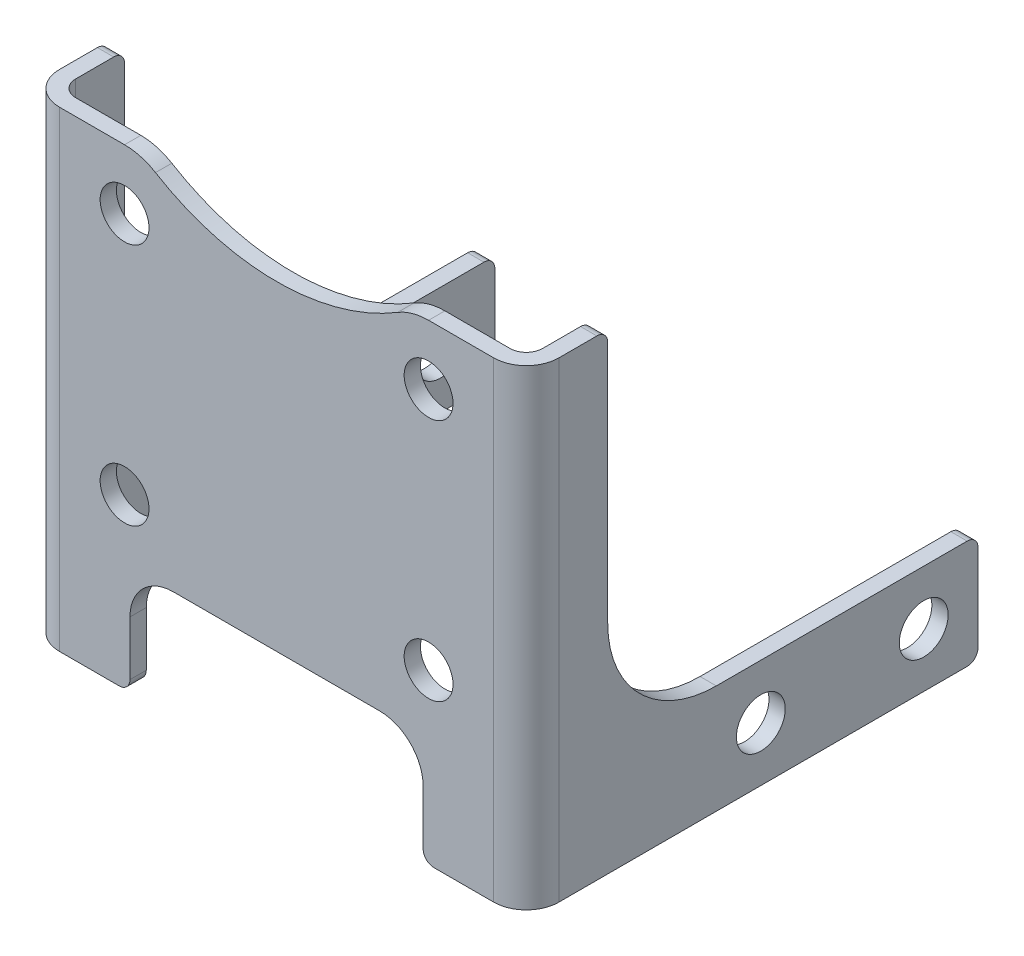
SolidWorks part; units mm, degrees
ref_plane "前视基准面" through (0, 0, 0) normal (0, 0, 1) x (1, 0, 0)
ref_plane "上视基准面" through (0, 0, 0) normal (0, 1, 0) x (1, 0, 0)
ref_plane "右视基准面" through (0, 0, 0) normal (1, 0, 0) x (0, 0, -1)
ref_plane "基准面1" through (0, 0, -40.1) normal (0, 0, -1) x (-1, 0, 0)
sketch "草图1" plane through (0, 0, -40.1) normal (0, 0, -1) x (-1, 0, 0)
  line L0 (-23, -17.5868) -> (-23, -61)
  line L1 (-23, -61) -> (23, -61)
  line L2 (23, -61) -> (23, -17.5868)
  line L3 (23, -17.5868) -> (-23, -17.5868)
extrude "凸台-拉伸1" add sketch "草图1" against normal blind 41.6
sketch "草图2" plane through (0, -61, 0) normal (0, -1, 0) x (1, 0, 0)
  line L0 (-21.5, -40.1) -> (21.5, -40.1)
  line L1 (21.5, -40.1) -> (21.5, 0)
  line L2 (21.5, 0) -> (-21.5, 0)
  line L3 (-21.5, 0) -> (-21.5, -40.1)
extrude "切除-拉伸1" cut sketch "草图2" against normal through all
sketch "草图3" plane through (0, 0, 1.5) normal (0, 0, 1) x (1, 0, 0)
  line L0 (-13.5, -61) -> (13.5, -61)
  line L1 (13.5, -61) -> (13.5, -51)
  line L2 (13.5, -51) -> (-13.5, -51)
  line L3 (-13.5, -51) -> (-13.5, -61)
extrude "切除-拉伸2" cut sketch "草图3" against normal through all
sketch "草图4" plane through (-21.5, 0, 0) normal (1, 0, 0) x (0, 0, -1)
  line L0 (40.1, -17.5868) -> (6, -17.5868)
  line L1 (6, -17.5868) -> (6, -51)
  line L2 (6, -51) -> (40.1, -51)
  line L3 (40.1, -51) -> (40.1, -17.5868)
extrude "切除-拉伸3" cut sketch "草图4" against normal through all
sketch "草图5" plane through (23, 0, 0) normal (1, 0, 0) x (0, 0, -1)
  line L0 (40.1, -17.5868) -> (6, -17.5868)
  line L1 (6, -17.5868) -> (6, -51)
  line L2 (6, -51) -> (40.1, -51)
  line L3 (40.1, -51) -> (40.1, -17.5868)
extrude "切除-拉伸4" cut sketch "草图5" against normal through all
sketch "草图6" plane through (0, 0, 1.5) normal (0, 0, 1) x (1, 0, 0)
  line L0 (12.3675, -17.5868) -> (-12.3675, -17.5868)
  arc A0 (-12.3675, -17.5868) -> (12.3675, -17.5868) centre (0, 0) ccw
extrude "切除-拉伸5" cut sketch "草图6" against normal through all
hole_wizard "Ø4.5 (4.5) 直径孔1" positions "草图8" profile "草图7" hole size "Ø4.5" standard "ANSI Metric"
sketch "草图8" plane through (-21.5, 0, 0) normal (1, 0, 0) x (0, 0, -1)
  point P0 (20.1, -56)
  point P1 (35.1, -56)
sketch "草图7" plane through (-21.5, -56, -20.1) normal (0, 1, 0) x (0, 0, -1)
  line L0 (0, 0) -> (0, 1.5)
  line L1 (0, 1.5) -> (2.25, 1.5)
  line L2 (2.25, 1.5) -> (2.25, 0)
  line L5 (2.25, 0) -> (0, 0)
  line L11 (0, -6.35) -> (0, 107.95) construction
  dimension "通孔孔直径" = 4.5
  dimension "通孔孔深度" = 1.5
hole_wizard "Ø4.5 (4.5) 直径孔2" positions "草图10" profile "草图9" hole size "Ø4.5" standard "ANSI Metric"
sketch "草图10" plane through (21.5, 0, 0) normal (-1, 0, 0) x (0, 0, 1)
  point P0 (-20.1, -56)
  point P1 (-35.1, -56)
sketch "草图9" plane through (21.5, -56, -20.1) normal (0, 1, 0) x (0, 0, 1)
  line L0 (0, 0) -> (0, 1.5)
  line L1 (0, 1.5) -> (2.25, 1.5)
  line L2 (2.25, 1.5) -> (2.25, 0)
  line L5 (2.25, 0) -> (0, 0)
  line L11 (0, -6.35) -> (0, 107.95) construction
  dimension "通孔孔直径" = 4.5
  dimension "通孔孔深度" = 1.5
hole_wizard "Ø4.5 (4.5) 直径孔3" positions "草图12" profile "草图11" hole size "Ø4.5" standard "ANSI Metric"
sketch "草图12" plane through (0, 0, 1.5) normal (0, 0, 1) x (1, 0, 0)
  point P0 (-14, -45.5)
  point P1 (-14, -23.0868)
  point P2 (14, -23.0868)
  point P3 (14, -45.5)
sketch "草图11" plane through (-14, -45.5, 1.5) normal (1, 0, 0) x (0, -1, 0)
  line L0 (0, 0) -> (0, 41.6)
  line L1 (0, 41.6) -> (2.25, 41.6)
  line L2 (2.25, 41.6) -> (2.25, 0)
  line L5 (2.25, 0) -> (0, 0)
  line L11 (0, -6.35) -> (0, 107.95) construction
  dimension "通孔孔直径" = 4.5
  dimension "通孔孔深度" = 41.6
fillet "圆角1" radius 1 8 edges at (-13.5, -61, 0.75) (22.25, -51, -40.1) (-22.25, -61, -40.1) (-22.25, -51, -40.1) (22.25, -61, -40.1) (22.25, -17.5868, -6) (-22.25, -17.5868, -6) (13.5, -61, 0.75)
fillet "圆角2" radius 1.5 2 edges at (-21.5, -39.2934, 0) (21.5, -39.2934, 0)
fillet "圆角3" radius 3 2 edges at (23, -39.2934, 1.5) (-23, -39.2934, 1.5)
fillet "圆角4" radius 4 2 edges at (13.5, -51, 0.75) (-13.5, -51, 0.75)
fillet "圆角5" radius 5.5 2 edges at (-12.3675, -17.5868, 0.75) (12.3675, -17.5868, 0.75)
fillet "圆角6" radius 10 2 edges at (-22.25, -51, -6) (22.25, -51, -6)
